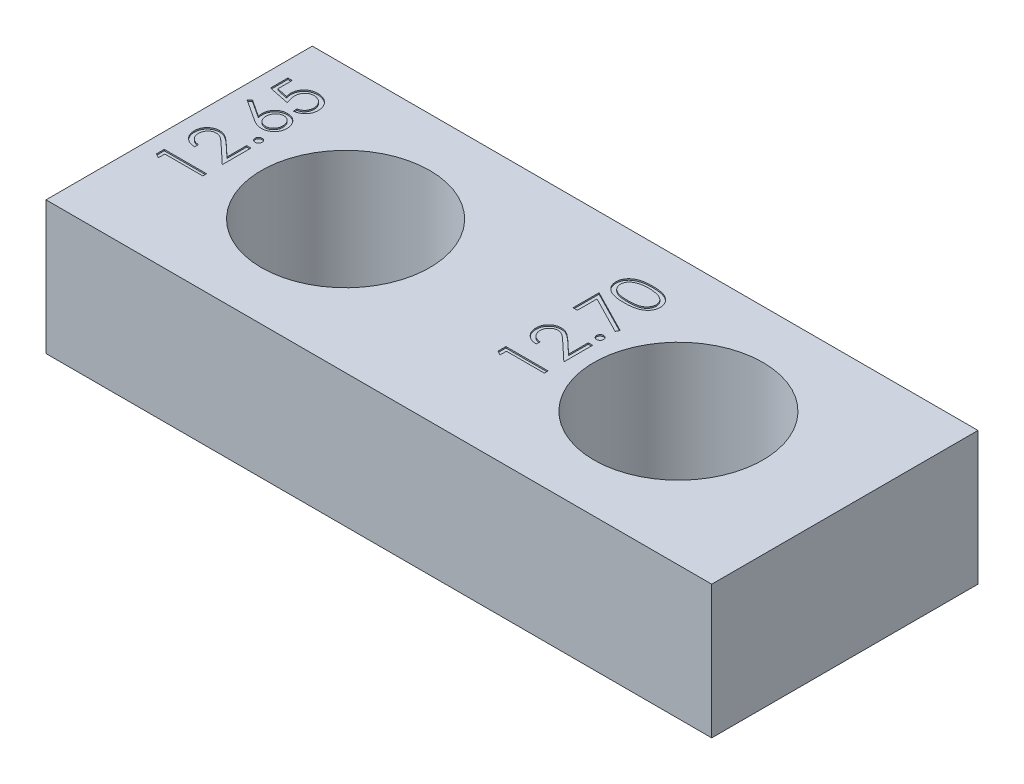
SolidWorks part; units mm, degrees
ref_plane "Front Plane" through (0, 0, 0) normal (0, 0, 1) x (1, 0, 0)
ref_plane "Top Plane" through (0, 0, 0) normal (0, 1, 0) x (1, 0, 0)
ref_plane "Right Plane" through (0, 0, 0) normal (1, 0, 0) x (0, 0, -1)
sketch "Sketch1" plane through (0, 0, 0) normal (0, 1, 0) x (1, 0, 0)
  line L0 (-12.5, 0) -> (12.5, 0) construction
  line L1 (25, -10) -> (-25, -10)
  line L2 (25, -10) -> (25, 10)
  line L3 (25, 10) -> (-25, 10)
  line L4 (-25, -10) -> (-25, 10)
  line L5 (25, -10) -> (-25, 10) construction
  line L6 (25, 10) -> (-25, -10) construction
  circle A0 centre (-12.5, 0) radius 6.325
  circle A1 centre (12.5, 0) radius 6.35
  point P0 (0, 0)
  point P10 (9.2686, 0)
  point P11 (0, 0)
  dimension "D3" = 12.65
  dimension "D4" = 12.7
  dimension "D1" = 50
  dimension "D2" = 20
  dimension "D5" = 25
extrude "Boss-Extrude1" add sketch "Sketch1" along normal blind 10
sketch "Sketch2" plane through (0, 10, 0) normal (0, 1, 0) x (1, 0, 0)
  line L0 (-20.6679, 7.3338) -> (-20.6679, -6.828) construction
  text T0 "12.65\r\n\r\n\r\n\r\n12.70"
  point P3 (-21.9457, -6.325)
  point P4 (-17.1541, 21.4424)
  point P5 (-21.5996, -7.813)
  point P6 (-21.5996, 6.269)
  point P7 (-21.5996, 7.6266)
  point P8 (-20.3485, 5.9229)
  point P9 (-20.6679, -6.828)
  point P10 (-20.6679, 7.3338)
extrude "Cut-Extrude1" cut sketch "Sketch2" against normal blind 0.1
